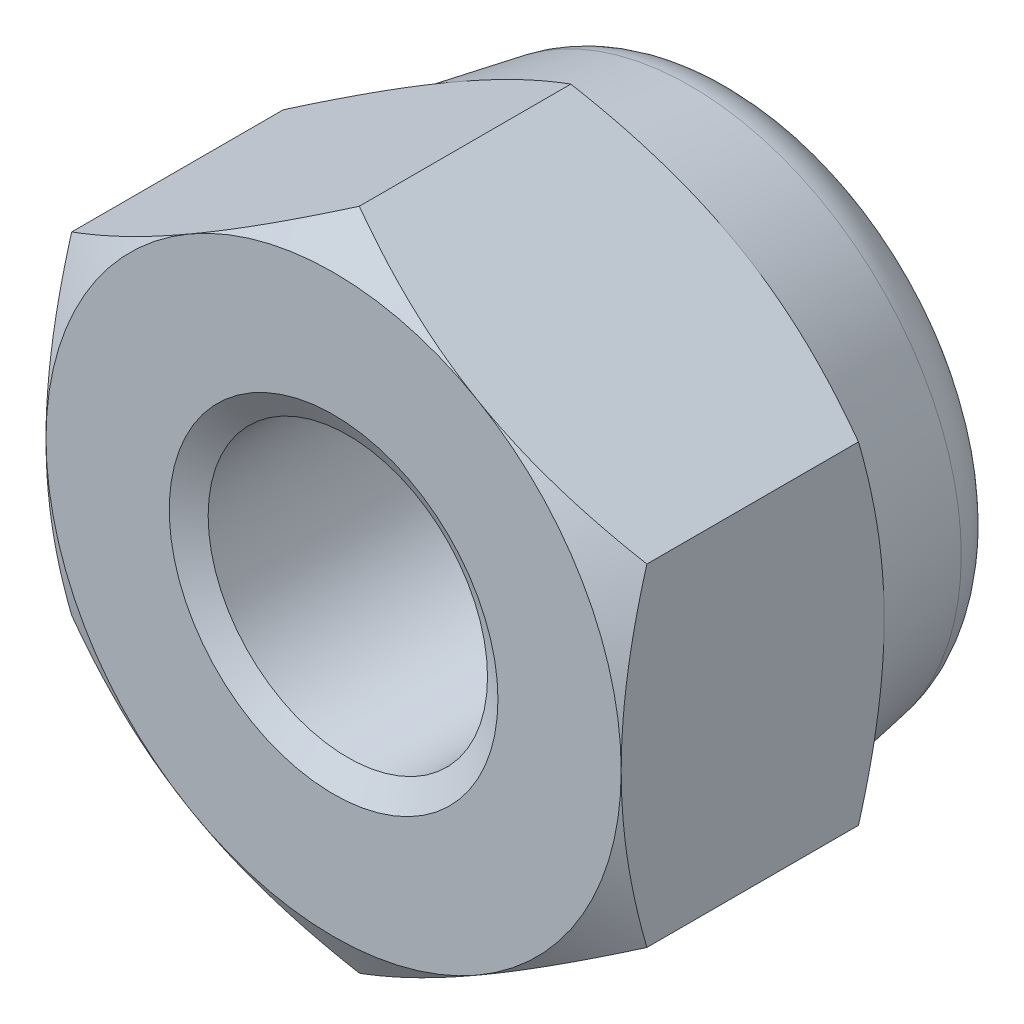
SolidWorks part; units mm, degrees
ref_plane "Přední rovina" through (0, 0, 0) normal (0, 0, 1) x (1, 0, 0)
ref_plane "Vrchní rovina" through (0, 0, 0) normal (0, 1, 0) x (1, 0, 0)
ref_plane "Pravá rovina" through (0, 0, 0) normal (1, 0, 0) x (0, 0, -1)
sketch "Skica1" plane through (0, 0, 0) normal (0, 0, 1) x (1, 0, 0)
  line L1 (3.5, -2.0207) -> (3.5, 2.0207)
  line L2 (3.5, 2.0207) -> (0, 4.0415)
  line L3 (0, 4.0415) -> (-3.5, 2.0207)
  line L4 (-3.5, 2.0207) -> (-3.5, -2.0207)
  line L5 (-3.5, -2.0207) -> (0, -4.0415)
  line L6 (0, -4.0415) -> (3.5, -2.0207)
  circle A0 centre (0, 0) radius 3.5 construction
  dimension "s" = 7
extrude "Vysunout1" add sketch "Skica1" along normal blind 3.2
sketch "Skica2" plane through (0, 0, 0) normal (0, 1, 0) x (1, 0, 0)
  line L0 (3.5, 0) -> (6.2713, 0)
  line L1 (6.2713, 0) -> (6.2713, -3.2)
  line L2 (6.2713, -3.2) -> (3.5, -3.2)
  line L3 (3.5, -3.2) -> (6.2713, -1.6)
  line L4 (6.2713, -1.6) -> (3.5, 0)
  line L5 (0, 0) -> (0, -3.2) construction
  dimension "D1" = 30
revolve "Odebrat otočením1" cut sketch "Skica2" angle 360 about L5
sketch "Skica3" plane through (0, 0, 0) normal (0, 0, -1) x (-1, 0, 0)
  arc A6 (-1.75, 3.0311) -> (-3.5, 0) centre (0, 0) ccw
  arc A7 (-3.5, 0) -> (-1.75, -3.0311) centre (0, 0) ccw
  arc A8 (-1.75, -3.0311) -> (1.75, -3.0311) centre (0, 0) ccw
  arc A9 (1.75, -3.0311) -> (3.5, 0) centre (0, 0) ccw
  arc A10 (3.5, 0) -> (1.75, 3.0311) centre (0, 0) ccw
  arc A11 (1.75, 3.0311) -> (-1.75, 3.0311) centre (0, 0) ccw
  arc A12 (-1.75, 3.0311) -> (-3.5, 0) centre (0, 0) ccw
  arc A13 (-3.5, 0) -> (-1.75, -3.0311) centre (0, 0) ccw
  arc A14 (-1.75, -3.0311) -> (1.75, -3.0311) centre (0, 0) ccw
  arc A15 (1.75, -3.0311) -> (3.5, 0) centre (0, 0) ccw
  arc A16 (3.5, 0) -> (1.75, 3.0311) centre (0, 0) ccw
  arc A17 (1.75, 3.0311) -> (-1.75, 3.0311) centre (0, 0) ccw
  dimension "D1" = 0
extrude "Vysunout2" add sketch "Skica3" along normal blind 1.8 draft 10
fillet "Zaoblit1" radius 0.8 1 edges at (-3.1826, 0, -1.8)
sketch "Skica4" plane through (0, 0, 0) normal (0, 1, 0) x (1, 0, 0)
  line L0 (0, 1.8) -> (0, -3.2) construction
  line L1 (2.5113, 1.8) -> (-2.5113, 1.8) construction
  line L2 (-1.75, -3.2) -> (1.75, -3.2) construction
  line L3 (-2, 1.8) -> (-2, -0.3)
  line L4 (-2, -0.3) -> (-1.7, -0.3)
  line L5 (-1.7, -0.3) -> (-1.7, -3.2)
  line L6 (-1.7, -3.2) -> (0, -3.2)
  line L7 (-2, 1.8) -> (0, 1.8)
  line L8 (0, 1.8) -> (0, -3.2)
  dimension "D1" = 3.4
  dimension "D2" = 4
  dimension "m3" = 2.9
revolve "Odebrat otočením2" cut sketch "Skica4" angle 360 about L0
cosmetic thread "Kosmetický závit1" parameters "D1"=2.9, "M"=4
sketch "Skica5" plane through (0, 0, 0.3) normal (0, 0, -1) x (-1, 0, 0)
  circle A0 centre (0, 0) radius 1.7 construction
  circle A1 centre (0, 0) radius 2
  circle A2 centre (0, 0) radius 2
  circle A3 centre (0, 0) radius 1.7
  dimension "D1" = 0
extrude "Vysunout3" add sketch "Skica5" along normal offset from surface (1.78 mm away) 0.32 separate body up to face at (-2, 0, -1.8)
sketch "Skica6" plane through (0, 0, 0) normal (0, 1, 0) x (1, 0, 0)
  line L0 (0, -3.2) -> (0, 1.8) construction
  line L1 (-1.75, -3.2) -> (1.75, -3.2) construction
  line L2 (2, 1.8) -> (-2, 1.8) construction
  line L3 (0, -2.0453) -> (2, -3.2)
  line L4 (1.75, -3.2) -> (3.5, -3.2) construction
  line L5 (2, -3.2) -> (0, -3.2)
  line L6 (0, -3.2) -> (0, -2.0453)
  dimension "D1" = 30
  dimension "D2" = 4
revolve "Odebrat otočením3" cut sketch "Skica6" angle 360 about L0
equation "\"D1@Kosmetický závit1\" = \"m3@Skica4\""
equation "\"D1@Vysunout3\" = 0.08 * \"D2@Skica4\""
equation "\"D2@Skica4\" = \"M@Kosmetický závit1\""
equation "\"D1@Zaoblit1\" = 0.2 * \"D2@Skica4\""
equation "\"D2@Skica6\" = \"M@Kosmetický závit1\""
equation "\"D1@Skica4\" = 0.85 * \"M@Kosmetický závit1\""
